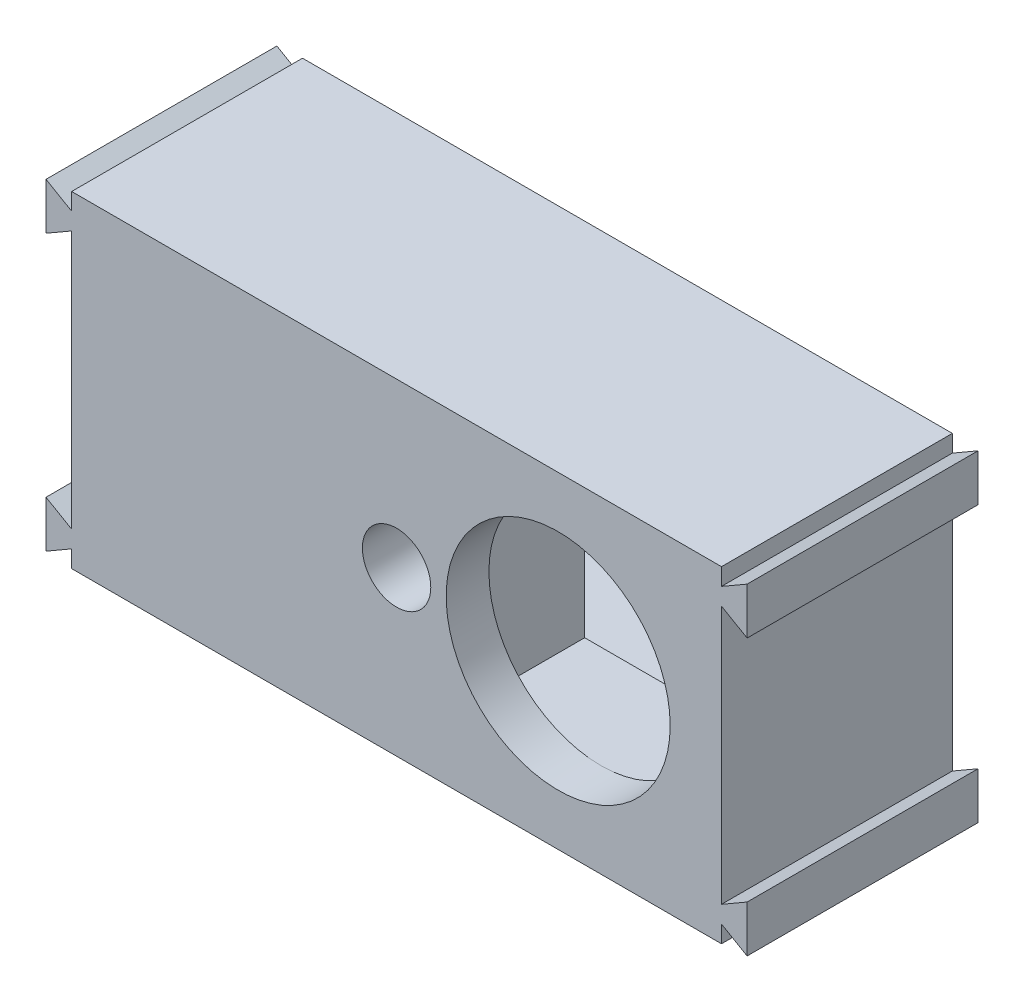
SolidWorks part; units mm, degrees
ref_plane "Front Plane" through (0, 0, 0) normal (0, 0, 1) x (1, 0, 0)
ref_plane "Top Plane" through (0, 0, 0) normal (0, 1, 0) x (1, 0, 0)
ref_plane "Right Plane" through (0, 0, 0) normal (1, 0, 0) x (0, 0, -1)
sketch "Sketch2" plane through (0, 0, 0) normal (0, 0, 1) x (1, 0, 0)
  line L0 (-19, 9.55) -> (-19, -9.55)
  line L1 (-16, 6.55) -> (16, 6.55) construction
  line L2 (-16, 6.55) -> (-16, -6.55) construction
  line L3 (-16, -6.55) -> (16, -6.55) construction
  line L4 (16, 6.55) -> (16, -6.55) construction
  line L5 (-16, 6.55) -> (16, -6.55) construction
  line L6 (-16, -6.55) -> (16, 6.55) construction
  line L7 (-19, -9.55) -> (19, -9.55)
  line L8 (19, 9.55) -> (19, -9.55)
  line L9 (-19, 9.55) -> (19, 9.55)
  circle A0 centre (9.45, 0) radius 6.55
  circle A1 centre (0, 0) radius 2
  point P0 (0, 0)
  point P14 (0, 0)
  point P15 (-16, 0)
  dimension "D5" = 4
  dimension "D1" = 32
  dimension "D2" = 13.1
  dimension "D4" = 16
  dimension "D3" = 3
extrude "Boss-Extrude1" add sketch "Sketch2" against normal blind 2.5
sketch "Sketch3" plane through (0, 0, -2.5) normal (0, 0, -1) x (-1, 0, 0)
  line L0 (-2.5, 6.55) -> (-2.5, -6.55)
  line L1 (19, 9.55) -> (-19, 9.55) construction
  line L2 (19, -9.55) -> (-19, -9.55) construction
  line L3 (-19, -9.55) -> (19, -9.55)
  line L4 (19, -9.55) -> (19, -5.55)
  line L5 (19, -5.55) -> (2.5, -5.55)
  line L6 (2.5, -5.55) -> (2.5, 5.55)
  line L7 (2.5, 5.55) -> (19, 5.55)
  line L9 (19, 9.55) -> (-19, 9.55)
  line L10 (19, 9.55) -> (19, -9.55) construction
  line L11 (16, 6.55) -> (-16, 6.55) construction
  line L12 (-2.5, 6.55) -> (-16, 6.55)
  line L13 (-16, 6.55) -> (-16, -6.55) construction
  line L14 (-16, 6.55) -> (-16, -6.55)
  line L16 (19, 9.55) -> (19, 5.55)
  line L17 (-2.5, -6.55) -> (-16, -6.55)
  line L18 (-19, 9.55) -> (-19, -9.55)
  line L19 (16, -6.55) -> (-16, -6.55) construction
  circle A0 centre (0, 0) radius 2 construction
  circle A1 centre (0, 0) radius 2
  point P20 (-2.9615, -6.55)
  dimension "D1" = 1
  dimension "D2" = 1
  dimension "D3" = 2.5
  dimension "D4" = 5
extrude "Boss-Extrude2" add sketch "Sketch3" along normal blind 6
sketch "Sketch4" plane through (0, 0, -8.5) normal (0, 0, -1) x (-1, 0, 0)
  line L4 (19, 5.55) -> (16.5, 5.55)
  line L5 (-19, -9.55) -> (19, -9.55)
  line L6 (-19, -9.55) -> (-19, 9.55)
  line L7 (-19, 9.55) -> (19, 9.55)
  line L8 (16.5, -7.05) -> (16.5, 7.05)
  line L9 (-16.5, -7.05) -> (16.5, -7.05)
  line L10 (-16.5, 7.05) -> (-16.5, -7.05)
  line L11 (16.5, 7.05) -> (-16.5, 7.05)
  line L12 (16.5, -7.05) -> (16.5, -5.55)
  line L13 (-16.5, -7.05) -> (16.5, -7.05)
  line L14 (-16.5, 7.05) -> (-16.5, -7.05)
  line L15 (16.5, 7.05) -> (-16.5, 7.05)
  line L16 (19, -9.55) -> (19, -5.55)
  line L17 (19, -5.55) -> (16.5, -5.55)
  line L18 (16.5, 5.55) -> (16.5, 7.05)
  line L19 (19, 5.55) -> (19, 9.55)
  dimension "D1" = 0.5
extrude "Boss-Extrude3" add sketch "Sketch4" along normal blind 5
sketch "Sketch5" plane through (0, 0, -13.5) normal (0, 0, -1) x (-1, 0, 0)
  line L0 (-19, 8.55) -> (-20.5, 9.416)
  line L1 (-19, 9.55) -> (-19, -9.55) construction
  line L2 (-20.5, 9.416) -> (-20.5, 6.684)
  line L3 (-20.5, 6.684) -> (-19, 7.55)
  line L4 (-19, 7.55) -> (-19, 8.55)
  line L5 (19, 9.55) -> (-19, 9.55) construction
  line L6 (7.425, 0) -> (-7.425, 0) construction
  line L7 (-19, -7.55) -> (-19, -8.55)
  line L8 (-20.5, -9.416) -> (-20.5, -6.684)
  line L9 (-20.5, -6.684) -> (-19, -7.55)
  line L10 (-19, -8.55) -> (-20.5, -9.416)
  dimension "D1" = 60
  dimension "D2" = 60
  dimension "D3" = 1
  dimension "D4" = 1.5
  dimension "D5" = 1
extrude "Boss-Extrude4" add sketch "Sketch5" against normal up to surface (13.5 mm away) up to face at (2, 0, 0)
mirror "Mirror1" about plane through (0, 0, 0) normal (1, 0, 0) of "Boss-Extrude4"
